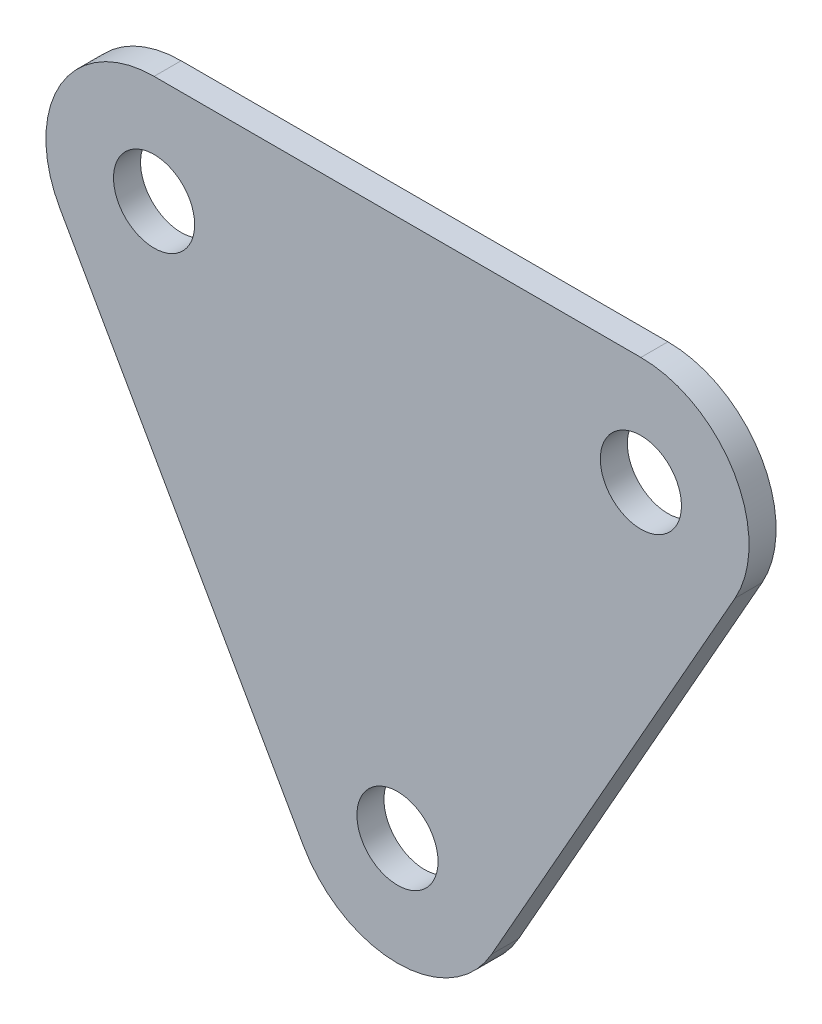
SolidWorks part; units mm, degrees
ref_plane "Front Plane" through (0, 0, 0) normal (0, 0, 1) x (1, 0, 0)
ref_plane "Top Plane" through (0, 0, 0) normal (0, 1, 0) x (1, 0, 0)
ref_plane "Right Plane" through (0, 0, 0) normal (1, 0, 0) x (0, 0, -1)
sketch "Sketch1" plane through (0, 0, 0) normal (0, 0, 1) x (1, 0, 0)
  line L0 (0, 0) -> (50000, 0) construction
  line L1 (0, 0) -> (0, -50000) construction
sketch "Sketch2" plane through (0, 0, 0) normal (0, 0, 1) x (1, 0, 0)
  line L0 (-200000, 0) -> (250000, 0) construction
  line L1 (180, -318) -> (180, 5.9942) construction
  line L2 (0, 80) -> (360, 80)
  line L3 (-69.6205, -39.4079) -> (110.3795, -357.4079)
  line L4 (429.6205, -39.4079) -> (249.6205, -357.4079)
  circle A0 centre (0, 0) radius 30
  circle A1 centre (360, 0) radius 30
  circle A2 centre (180, -318) radius 30
  arc A3 (0, 80) -> (-69.6205, -39.4079) centre (0, 0) ccw
  arc A4 (429.6205, -39.4079) -> (360, 80) centre (360, 0) ccw
  arc A5 (110.3795, -357.4079) -> (249.6205, -357.4079) centre (180, -318) ccw
  dimension "D1" = 360
  dimension "D2" = 318
  dimension "D3" = 180
extrude "Boss-Extrude1" add sketch "Sketch2" along normal blind 20
